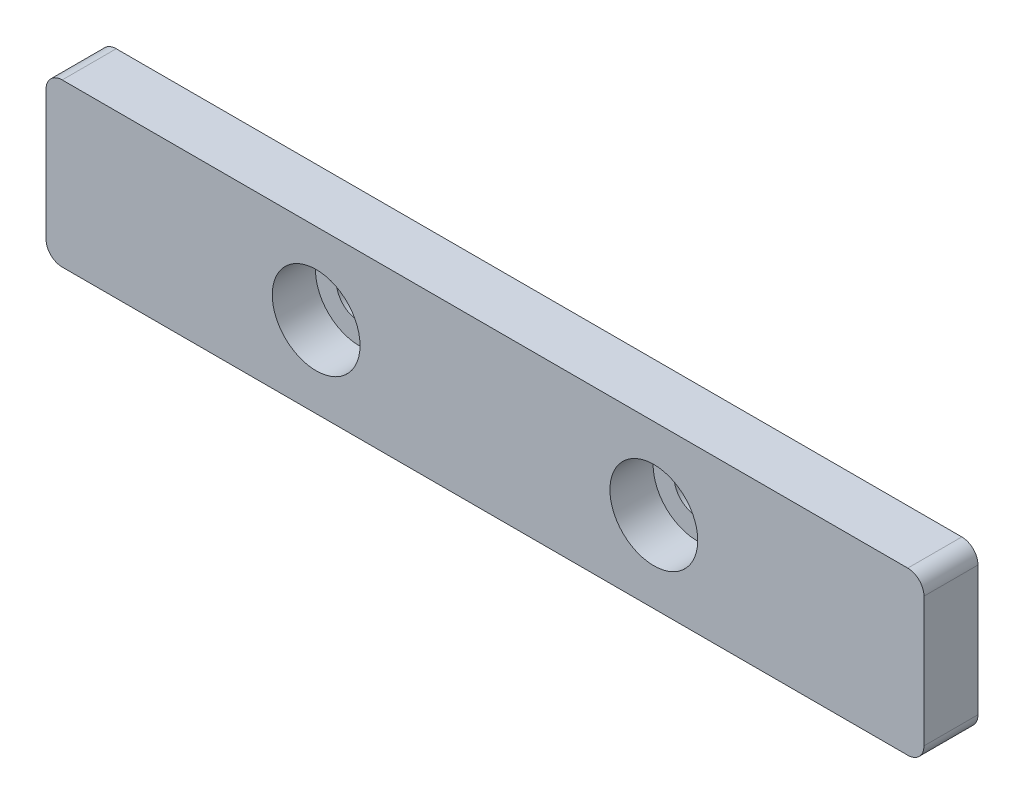
SolidWorks part; units mm, degrees
ref_plane "Ebene vorne" through (0, 0, 0) normal (0, 0, 1) x (1, 0, 0)
ref_plane "Ebene oben" through (0, 0, 0) normal (0, 1, 0) x (1, 0, 0)
ref_plane "Ebene rechts" through (0, 0, 0) normal (1, 0, 0) x (0, 0, -1)
sketch "Skizze2" plane through (0, 0, 18) normal (0, 0, 1) x (1, 0, 0)
  line L1 (1.7897, 17.8177) -> (66.7897, 17.8177)
  line L2 (1.7897, 17.8177) -> (1.7897, 5.8177)
  line L3 (1.7897, 5.8177) -> (66.7897, 5.8177)
  line L4 (66.7897, 17.8177) -> (66.7897, 5.8177)
extrude "Aufsatz-Linear austragen1" add sketch "Skizze2" along normal blind 4
sketch "Skizze3" plane through (0, 0, 22) normal (0, 0, 1) x (1, 0, 0)
  circle A0 centre (21.7897, 11.8177) radius 1.7
  circle A1 centre (46.7897, 11.8177) radius 1.7
  dimension "D1" = 3.4
extrude "Schnitt-Linear austragen1" cut sketch "Skizze3" against normal through all
sketch "Skizze4" plane through (0, 0, 22) normal (0, 0, 1) x (1, 0, 0)
  circle A0 centre (21.7897, 11.8177) radius 3.25
  circle A1 centre (46.7897, 11.8177) radius 3.25
  dimension "D1" = 6.5
extrude "Schnitt-Linear austragen2" cut sketch "Skizze4" against normal blind 3.2
fillet "Verrundung3" radius 1.2 4 edges at (66.7897, 5.8177, 20) (66.7897, 17.8177, 20) (1.7897, 5.8177, 20) (1.7897, 17.8177, 20)
